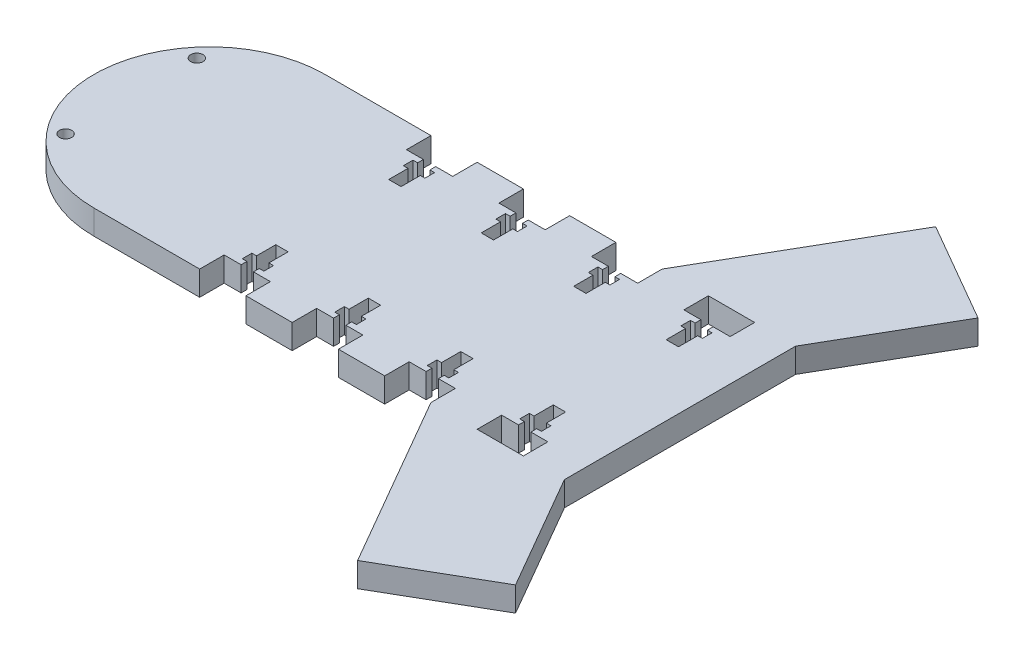
SolidWorks part; units mm, degrees
ref_plane "Front Plane" through (0, 0, 0) normal (0, 0, 1) x (1, 0, 0)
ref_plane "Top Plane" through (0, 0, 0) normal (0, 1, 0) x (1, 0, 0)
ref_plane "Right Plane" through (0, 0, 0) normal (1, 0, 0) x (0, 0, -1)
sketch "Sketch1" plane through (0, 0, 0) normal (0, 1, 0) x (1, 0, 0)
  line L0 (0, 30) -> (87.469, 30)
  line L1 (87.469, 30) -> (113.4497, 75)
  line L2 (113.4497, 75) -> (139.4305, 60)
  line L3 (139.4305, 60) -> (122.11, 30)
  line L4 (122.11, 30) -> (122.11, -30)
  line L5 (122.11, -30) -> (139.4305, -60)
  line L6 (139.4305, -60) -> (113.4497, -75)
  line L7 (113.4497, -75) -> (87.469, -30)
  line L8 (87.469, -30) -> (0, -30)
  arc A0 (0, 30) -> (0, -30) centre (0, 0) ccw
  dimension "D1" = 30
  dimension "D2" = 30
  dimension "D3" = 150
  dimension "D4" = 122.11
  dimension "D5" = 30
extrude "Boss-Extrude1" add sketch "Sketch1" along normal blind 6.35
sketch "Sketch2" plane through (0, 6.35, 0) normal (0, 1, 0) x (1, 0, 0)
  line L0 (87.469, 30) -> (0, 30) construction
  line L1 (75.469, 30) -> (87.469, 30)
  line L2 (75.469, 30) -> (75.469, 23.65)
  line L3 (75.469, 23.65) -> (87.469, 23.65)
  line L4 (87.469, 30) -> (87.469, 23.65)
  dimension "D1" = 6.35
  dimension "D2" = 12
extrude "Cut-Extrude1" cut sketch "Sketch2" against normal up to next
pattern_linear "LPattern2" count 3 spacing 24 along (-1, 0, 0) of "Cut-Extrude1"
pattern_linear "LPattern6" count 2 spacing 24 along (1, 0, 0) of "Cut-Extrude1"
mirror "Mirror5" about plane through (0, 0, 0) normal (0, 0, 1) of "LPattern2", "Cut-Extrude1"
sketch "Sketch4" plane through (0, 6.35, 0) normal (0, 1, 0) x (1, 0, 0)
  line L0 (111.469, 23.65) -> (111.469, 30) construction
  line L1 (99.469, -30) -> (111.469, -30)
  line L2 (99.469, -30) -> (99.469, -23.65)
  line L3 (99.469, -23.65) -> (111.469, -23.65)
  line L4 (111.469, -30) -> (111.469, -23.65)
  line L5 (99.469, 30) -> (99.469, 23.65) construction
  line L6 (75.469, -23.65) -> (87.469, -23.65) construction
extrude "Cut-Extrude2" cut sketch "Sketch4" against normal up to next
sketch "Sketch5" plane through (0, 6.35, 0) normal (0, 1, 0) x (1, 0, 0)
  line L0 (0, 0) -> (122.11, 0) construction
  line L1 (122.11, -30) -> (122.11, 30) construction
  line L2 (31.869, 23.65) -> (31.869, 22.15)
  line L3 (27.469, 23.65) -> (39.469, 23.65) construction
  line L4 (31.869, 22.15) -> (30.669, 22.15)
  line L5 (30.669, 22.15) -> (30.669, 19.65)
  line L6 (30.669, 19.65) -> (31.869, 19.65)
  line L7 (31.869, 19.65) -> (31.869, 14.65)
  line L8 (31.869, 14.65) -> (35.069, 14.65)
  line L9 (35.069, 14.65) -> (35.069, 19.65)
  line L10 (35.069, 19.65) -> (36.269, 19.65)
  line L11 (36.269, 19.65) -> (36.269, 22.15)
  line L12 (36.269, 22.15) -> (35.069, 22.15)
  line L13 (35.069, 22.15) -> (35.069, 23.65)
  line L14 (35.069, 23.65) -> (31.869, 23.65)
  line L15 (33.469, 23.65) -> (33.469, 14.65) construction
  point P21 (33.469, 23.65)
  point P22 (35.069, 19.5882)
  dimension "D1" = 9
  dimension "D2" = 2.5
  dimension "D3" = 1.6
  dimension "D4" = 2.8
  dimension "D5" = 2.8
  dimension "D6" = 1.5
extrude "Cut-Extrude3" cut sketch "Sketch5" against normal up to next
pattern_linear "LPattern9" count 4 spacing 24 along (1, 0, 0) of "Cut-Extrude3"
mirror "Mirror14" about plane through (0, 0, 0) normal (0, 0, 1) of "LPattern9", "Cut-Extrude3"
sketch "Sketch6" plane through (0, 6.35, 0) normal (0, 1, 0) x (1, 0, 0)
  line L0 (-30, 0) -> (0, 0) construction
  line L1 (0, 0) -> (-28.9437, -24.2867) construction
  circle A0 centre (-20.3002, -17.0339) radius 1.6
  circle A1 centre (-20.3002, 17.0339) radius 1.6
  arc A2 (0, 30) -> (0, -30) centre (0, 0) ccw construction
  dimension "D1" = 3.2
  dimension "D3" = 40
  dimension "D2" = 26.5
extrude "Cut-Extrude4" cut sketch "Sketch6" against normal up to next
